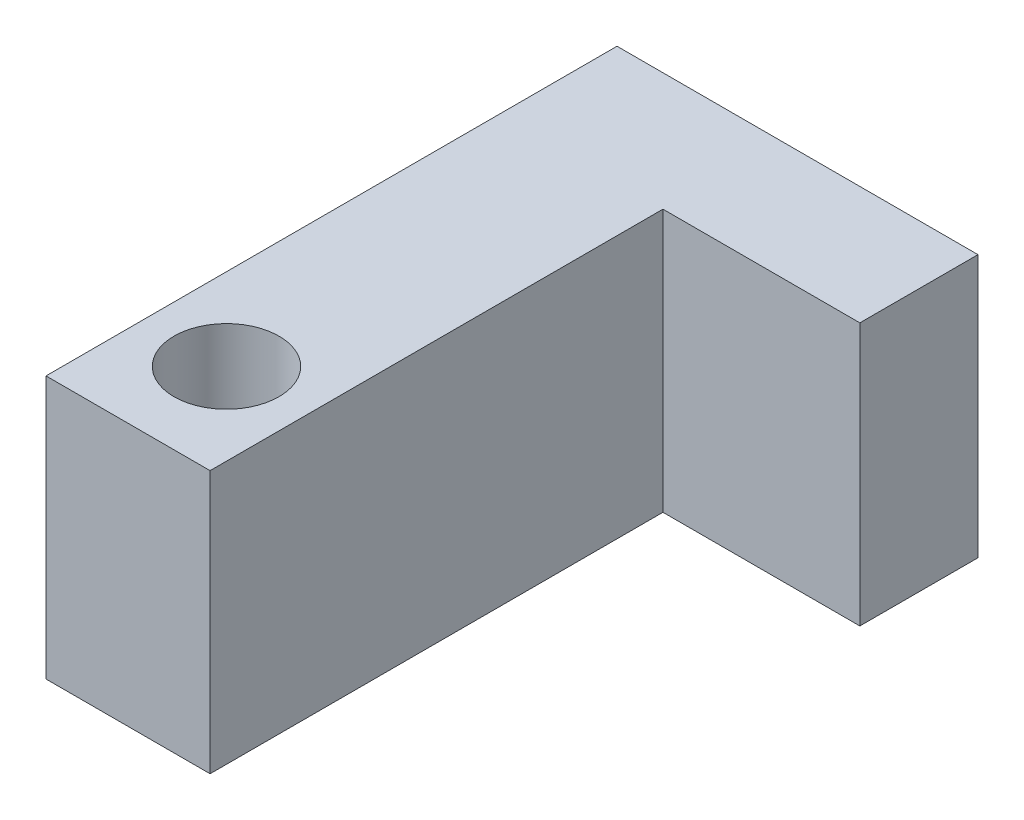
SolidWorks part; units mm, degrees
ref_plane "Front Plane" through (0, 0, 0) normal (0, 0, 1) x (1, 0, 0)
ref_plane "Top Plane" through (0, 0, 0) normal (0, 1, 0) x (1, 0, 0)
ref_plane "Right Plane" through (0, 0, 0) normal (1, 0, 0) x (0, 0, -1)
sketch "Sketch1" plane through (0, 0, 0) normal (0, 1, 0) x (1, 0, 0)
  line L0 (-43.144, 25.2592) -> (-43.144, 29.6092)
  line L4 (-43.144, 29.6092) -> (-40.394, 29.6092)
  line L5 (-43.144, 25.2592) -> (-41.894, 25.2592)
  line L6 (-41.894, 25.2592) -> (-41.894, 28.7092)
  line L7 (-41.894, 28.7092) -> (-40.394, 28.7092)
  line L8 (-40.394, 28.7092) -> (-40.394, 29.6092)
  line L9 (-42.519, 25.2592) -> (-42.519, 26.0092)
  circle A0 centre (-42.519, 26.0092) radius 0.4
extrude "Boss-Extrude1" add sketch "Sketch1" along normal blind 2
